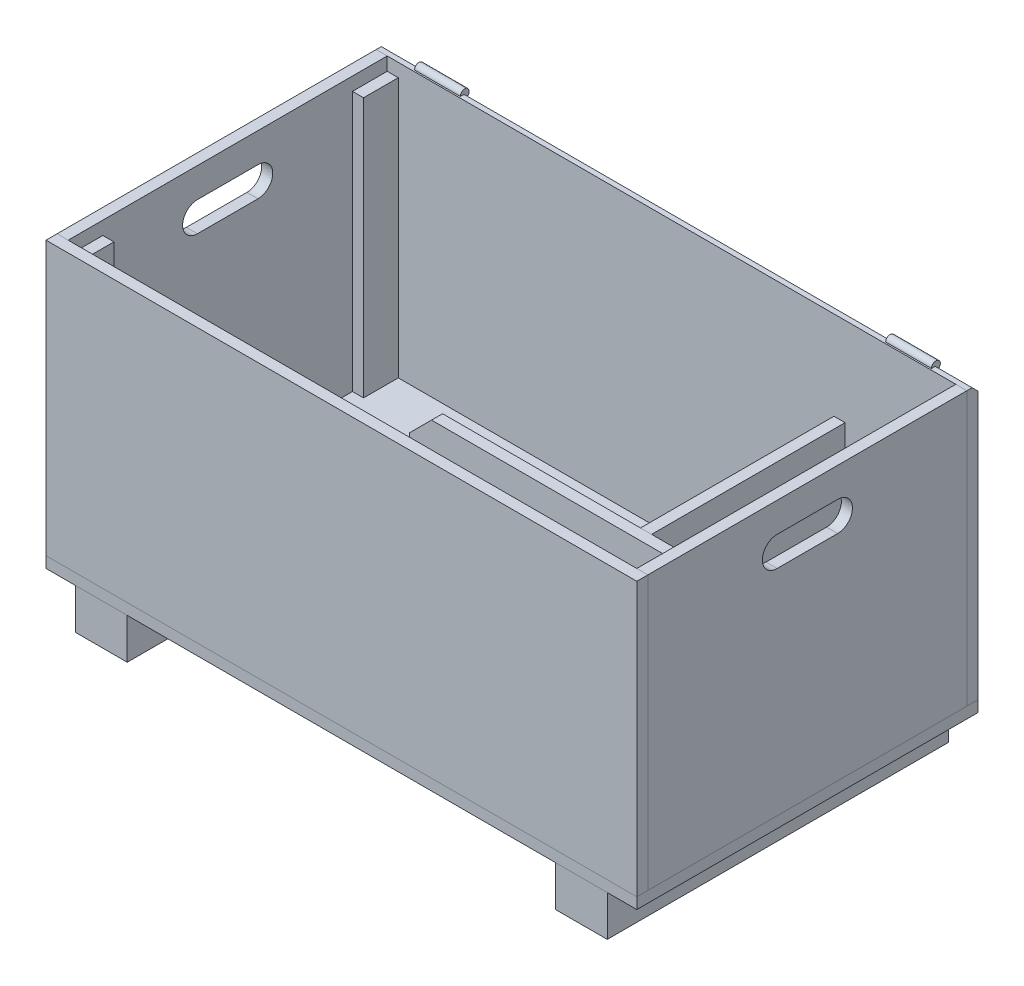
SolidWorks part; units mm, degrees
material "Pin"
ref_plane "Front" through (0, 0, 0) normal (0, 0, 1) x (1, 0, 0)
ref_plane "Top" through (0, 0, 0) normal (0, 1, 0) x (1, 0, 0)
ref_plane "Right" through (0, 0, 0) normal (1, 0, 0) x (0, 0, -1)
sketch "Esquisse1" plane through (0, 0, 0) normal (0, 1, 0) x (1, 0, 0)
  line L1 (-400, -231) -> (400, -231)
  line L2 (-400, -231) -> (-400, 231)
  line L3 (-400, 231) -> (400, 231)
  line L4 (400, -231) -> (400, 231)
  line L5 (0, 231) -> (0, -231) construction
  line L6 (-400, 0) -> (400, 0) construction
  point P0 (0, 0)
  dimension "D1" = 462
  dimension "D2" = 800
extrude "Boss.-Extru.1" add sketch "Esquisse1" along normal blind 15
sketch "Esquisse2" plane through (0, 0, 231) normal (0, 0, 1) x (1, 0, 0)
  line L0 (-400, 0) -> (400, 0) construction
  line L1 (-360, 0) -> (-290, 0)
  line L2 (-360, 0) -> (-360, -55)
  line L3 (-360, -55) -> (-290, -55)
  line L4 (-290, 0) -> (-290, -55)
  line L5 (0, -50) -> (0, 50) construction
  line L6 (290, 0) -> (290, -55)
  line L7 (360, -55) -> (290, -55)
  line L8 (360, 0) -> (360, -55)
  line L9 (360, 0) -> (290, 0)
  line L10 (-400, 15) -> (-400, 0) construction
  dimension "D1" = 70
  dimension "D2" = 55
  dimension "D3" = 40
  dimension "D4" = 580
extrude "Boss.-Extru.2" add sketch "Esquisse2" against normal up to surface (462 mm away) separate body up to face at (0, 7.5, -231)
sketch "Esquisse3" plane through (0, 15, 0) normal (0, 1, 0) x (1, 0, 0)
  line L0 (400, -231) -> (400, 231) construction
  line L1 (-400, 231) -> (400, 231)
  line L2 (-400, 231) -> (-400, 216)
  line L3 (-400, 216) -> (400, 216)
  line L4 (400, 231) -> (400, 216)
  line L5 (-50, 0) -> (50, 0) construction
  line L6 (400, -231) -> (400, -216)
  line L7 (-400, -216) -> (400, -216)
  line L8 (-400, -231) -> (-400, -216)
  line L9 (-400, -231) -> (400, -231)
  dimension "D1" = 15
extrude "Boss.-Extru.3" add sketch "Esquisse3" along normal blind 370 separate body
sketch "Esquisse4" plane through (0, 15, 0) normal (0, 1, 0) x (1, 0, 0)
  line L0 (400, -216) -> (-400, -216) construction
  line L1 (-400, 216) -> (-385, 216)
  line L2 (-400, 216) -> (-400, -216)
  line L3 (-400, -216) -> (-385, -216)
  line L4 (-385, 216) -> (-385, -216)
  line L5 (-400, -216) -> (-400, -231) construction
  line L6 (400, 216) -> (385, 216)
  line L7 (400, 216) -> (400, -216)
  line L8 (400, -216) -> (385, -216)
  line L9 (385, 216) -> (385, -216)
extrude "Boss.-Extru.4" add sketch "Esquisse4" along normal up to vertex (370 mm away) separate body
sketch "Esquisse5" plane through (0, 15, 0) normal (0, 1, 0) x (1, 0, 0)
  line L0 (-50, 0) -> (50, 0) construction
  line L1 (-385, 216) -> (-370, 216)
  line L2 (-385, 216) -> (-385, 169)
  line L3 (-385, 169) -> (-370, 169)
  line L4 (-370, 216) -> (-370, 169)
  line L5 (-370, -216) -> (-370, -169)
  line L6 (-385, -169) -> (-370, -169)
  line L7 (-385, -216) -> (-385, -169)
  line L8 (-385, -216) -> (-370, -216)
  line L9 (0, -50) -> (0, 50) construction
  line L10 (385, -216) -> (370, -216)
  line L11 (385, -216) -> (385, -169)
  line L12 (385, -169) -> (370, -169)
  line L13 (370, -216) -> (370, -169)
  line L14 (370, 216) -> (370, 169)
  line L15 (385, 169) -> (370, 169)
  line L16 (385, 216) -> (385, 169)
  line L17 (385, 216) -> (370, 216)
  dimension "D1" = 15
  dimension "D2" = 47
extrude "Boss.-Extru.5" add sketch "Esquisse5" along normal offset from surface (352 mm away) 18 separate body up to face at (0, 385, -223.5)
sketch "Esquisse6" plane through (-400, 0, 0) normal (-1, 0, 0) x (0, 0, 1)
  line L0 (-41, 325) -> (41, 325) construction
  line L1 (-41, 345) -> (41, 345)
  line L2 (-41, 305) -> (41, 305)
  line L3 (-231, 385) -> (-231, 15) construction
  line L4 (-216, 385) -> (216, 385) construction
  arc A0 (-41, 345) -> (-41, 305) centre (-41, 325) ccw
  arc A1 (41, 305) -> (41, 345) centre (41, 325) ccw
  point P2 (0, 325)
  dimension "D1" = 190
  dimension "D2" = 60
  dimension "D3" = 40
extrude "Enlèv. mat.-Extru.1" cut sketch "Esquisse6" against normal through all
sketch "Esquisse7" plane through (0, 15, 0) normal (0, 1, 0) x (1, 0, 0)
  line L0 (-351.6092, 171) -> (-330, 190.3402)
  line L1 (-351.6092, 171) -> (-199.4593, 1)
  line L2 (-330, 190.3402) -> (-180, 22.7423)
  line L3 (-30, -188.3402) -> (-8.3908, -169)
  line L4 (-351.6092, -169) -> (-330, -188.3402)
  line L5 (-351.6092, -169) -> (-199.4593, 1)
  line L6 (-330, -188.3402) -> (-180, -20.7423)
  line L7 (-30, 190.3402) -> (-8.3908, 171)
  line L8 (35, 195.3565) -> (13.4054, 176)
  line L9 (35, 195.3565) -> (187.7919, 24.8983)
  line L10 (13.4054, 176) -> (167.7865, 3.7689)
  line L11 (361.5946, -169) -> (340, -188.3565)
  line L12 (345, 190.9384) -> (366.0585, 171)
  line L13 (345, 190.9384) -> (187.7919, 24.8983)
  line L14 (366.0585, 171) -> (207.2135, 3.2311)
  line L15 (8.9415, -164) -> (30, -183.9384)
  line L16 (-370, 169) -> (-370, 216) construction
  line L17 (-370, -216) -> (-370, -169) construction
  line L18 (-400, 216) -> (400, 216) construction
  line L19 (400, -216) -> (-400, -216) construction
  line L20 (-180, 22.7423) -> (-30, 190.3402)
  line L21 (-160.5407, 1) -> (-8.3908, 171)
  line L22 (-160.5407, 1) -> (-8.3908, -169)
  line L23 (-180, -20.7423) -> (-30, -188.3402)
  line L24 (167.7865, 3.7689) -> (8.9415, -164)
  line L25 (187.2081, -17.8983) -> (30, -183.9384)
  line L26 (207.2135, 3.2311) -> (361.5946, -169)
  line L27 (187.2081, -17.8983) -> (340, -188.3565)
  dimension "D1" = 29
  dimension "D2" = 40
  dimension "D3" = 340
  dimension "D4" = 405
  dimension "D5" = 715
  dimension "D6" = 40
  dimension "D7" = 340
  dimension "D8" = 400
  dimension "D9" = 710
  dimension "D10" = 45
  dimension "D11" = 385
  dimension "D12" = 47
  dimension "D13" = 45
  dimension "D14" = 385
  dimension "D15" = 40
  dimension "D16" = 380
  dimension "D17" = 385
  dimension "D18" = 45
  dimension "D19" = 482.2425
  dimension "D20" = 482.2425
  dimension "D21" = 489.3053
  dimension "D22" = 488.7909
extrude "Boss.-Extru.6" [suppressed] add sketch "Esquisse7" along normal blind 27 separate body
sketch "Esquisse8" plane through (-400, 0, 0) normal (-1, 0, 0) x (0, 0, 1)
  line L0 (-231, 385) -> (-216, 385) construction
  line L1 (-216, 385) -> (-216, 15) construction
  circle A0 centre (-224, 385) radius 6
  dimension "D1" = 12
  dimension "D2" = 8
extrude "Boss.-Extru.7" add sketch "Esquisse8" against normal blind 62 from offset 50 separate body offset against normal yes
mirror "Symétrie3" about plane through (0, 0, 0) normal (1, 0, 0) of bodies 116
chamfer "Chanfrein1" distance 8 angle 45 1 edges at (0, 385, -231)
sketch "Esquisse9" plane through (0, 15, 0) normal (0, 1, 0) x (1, 0, 0)
  line L0 (400, -216) -> (-400, -216) construction
  line L1 (-78, -216) -> (-63, -216)
  line L2 (-78, -216) -> (-78, -61)
  line L3 (-78, -61) -> (-63, -61)
  line L4 (-63, -216) -> (-63, -61)
  line L6 (370, -216) -> (355, -216)
  line L7 (370, -216) -> (370, -61)
  line L8 (370, -61) -> (355, -61)
  line L9 (355, -216) -> (355, -61)
  dimension "D1" = 448
  dimension "D2" = 15
  dimension "D3" = 155
extrude "Boss.-Extru.8" add sketch "Esquisse9" along normal blind 130 separate body
sketch "Esquisse10" plane through (0, 15, 0) normal (0, 1, 0) x (1, 0, 0)
  line L0 (385, 216) -> (385, -216) construction
  line L1 (-78, -61) -> (385, -61)
  line L2 (-78, -61) -> (-78, -46)
  line L3 (-78, -46) -> (385, -46)
  line L4 (385, -61) -> (385, -46)
  dimension "D1" = 15
extrude "Boss.-Extru.9" add sketch "Esquisse10" along normal blind 250 separate body
sketch "Esquisse11" plane through (0, 15, 0) normal (0, 1, 0) x (1, 0, 0)
  line L0 (-400, 216) -> (400, 216) construction
  line L1 (220, 216) -> (235, 216)
  line L2 (220, 216) -> (220, -46)
  line L3 (220, -46) -> (235, -46)
  line L4 (235, 216) -> (235, -46)
  line L5 (385, -46) -> (-78, -46) construction
  line L6 (385, 216) -> (385, -216) construction
  dimension "D1" = 15
  dimension "D2" = 165
extrude "Boss.-Extru.10" add sketch "Esquisse11" along normal up to surface (250 mm away) separate body up to face at (153.5, 265, 53.5)
chamfer "Chanfrein2" distance 30 angle 45 1 edges at (-78, 265, 53.5)
sketch "Esquisse12" plane through (0, 15, 0) normal (0, 1, 0) x (1, 0, 0)
  line L0 (-48.5, 65) -> (72, 65) construction
  line L1 (72, 65) -> (72, 123.5) construction
  line L2 (-195, 140.5) -> (-195, -15) construction
  line L3 (-195, -15) -> (-243.5, -15) construction
  line L4 (-400, 216) -> (400, 216) construction
  line L5 (-400, 216) -> (400, 216) construction
  line L6 (-385, -216) -> (-385, 216) construction
  line L7 (-385, -216) -> (-385, 216) construction
  circle A0 centre (-243.5, 140.5) radius 1
  circle A1 centre (-48.5, 123.5) radius 1
  circle A2 centre (-146.5, 140.5) radius 1
  circle A3 centre (192.5, 123.5) radius 1
  circle A4 centre (-48.5, 6.5) radius 1
  circle A5 centre (192.5, 6.5) radius 1
  circle A6 centre (-243.5, -170.5) radius 1
  circle A7 centre (-146.5, -170.5) radius 1
  circle A8 centre (-340, -15) radius 1
  dimension "D1" = 97
  dimension "D2" = 241
  dimension "D3" = 117
  dimension "D4" = 311
  dimension "D5" = 75.5
  dimension "D7" = 92.5
  dimension "D9" = 141.5
  dimension "D11" = 336.5
  dimension "D13" = 2
  dimension "D14" = 45
  dimension "D6" = 231
  dimension "D8" = 151
  dimension "D10" = 190
  dimension "D12" = 457
extrude "Enlèv. mat.-Extru.2" cut sketch "Esquisse12" against normal up to surface (15 mm away) up to face at (0, 0, 0)
